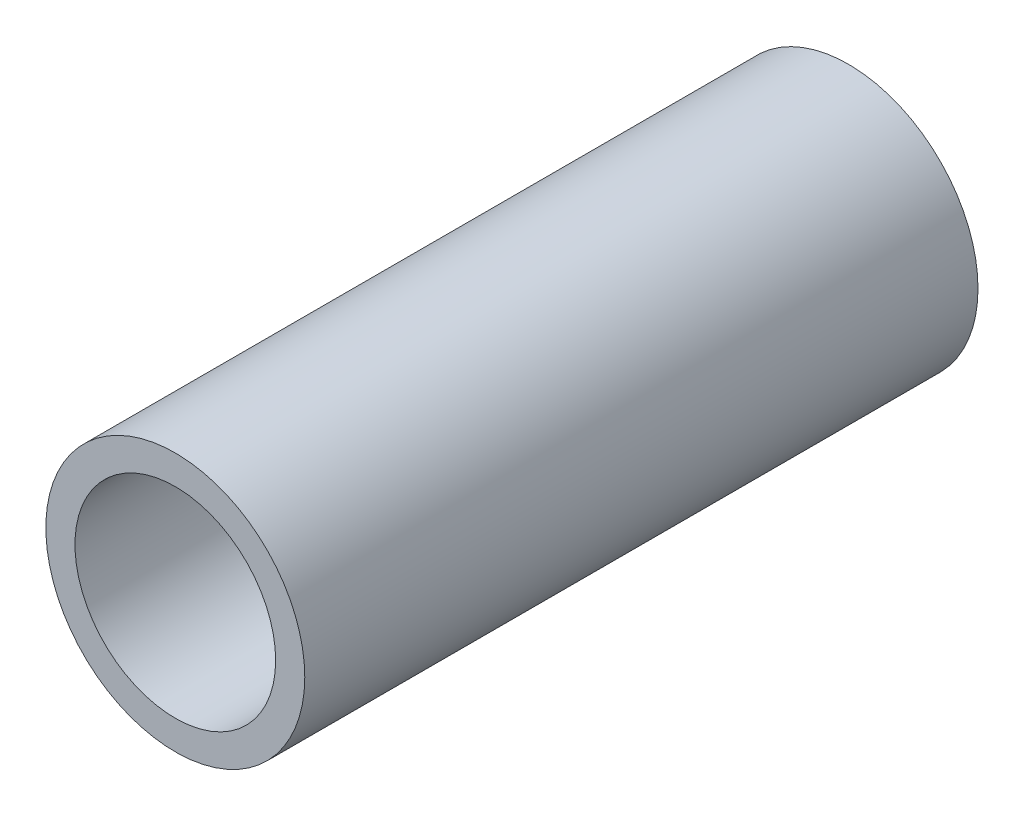
SolidWorks part; units mm, degrees
ref_plane "Спереди" through (0, 0, 0) normal (0, 0, 1) x (1, 0, 0)
ref_plane "Сверху" through (0, 0, 0) normal (0, 1, 0) x (1, 0, 0)
ref_plane "Справа" through (0, 0, 0) normal (1, 0, 0) x (0, 0, -1)
sketch "Эскиз1" plane through (0, 0, 0) normal (0, 0, 1) x (1, 0, 0)
  circle A0 centre (0, 0) radius 1
  circle A1 centre (0, 0) radius 0.775
extrude "Бобышка-Вытянуть1" add sketch "Эскиз1" along normal blind 5.2
